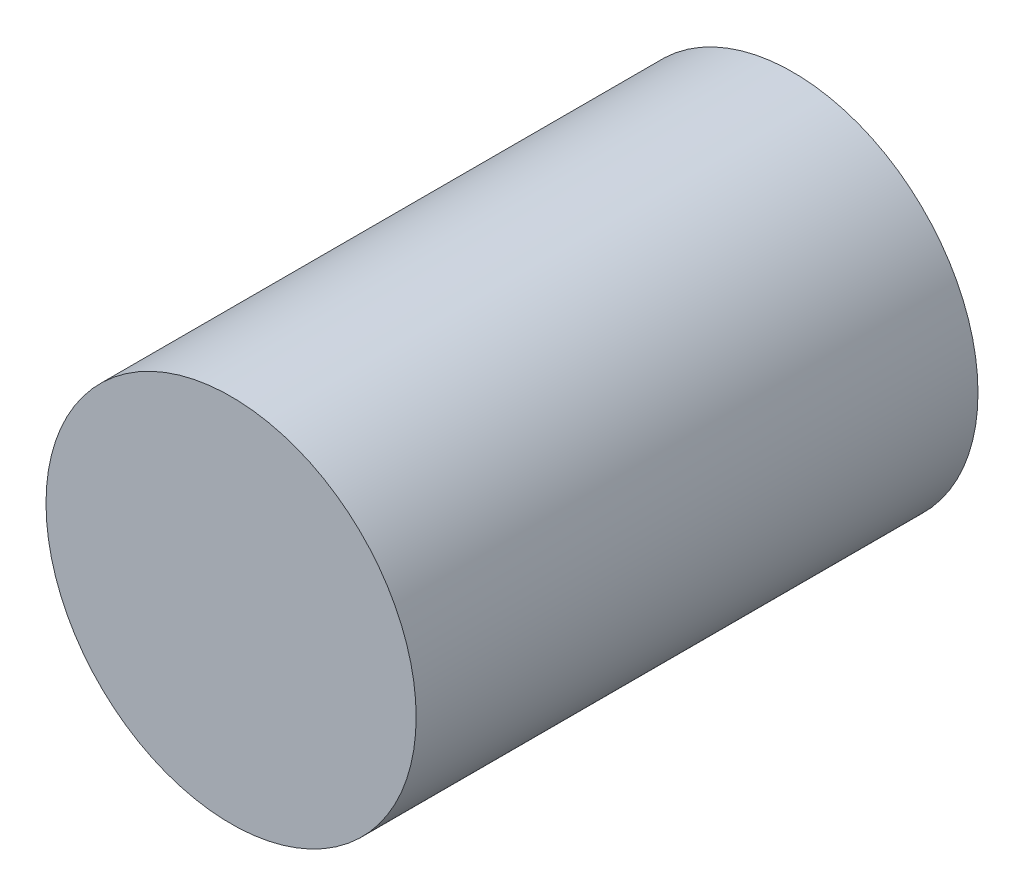
SolidWorks part; units mm, degrees
ref_plane "前视基准面" through (0, 0, 0) normal (0, 0, 1) x (1, 0, 0)
ref_plane "上视基准面" through (0, 0, 0) normal (0, 1, 0) x (1, 0, 0)
ref_plane "右视基准面" through (0, 0, 0) normal (1, 0, 0) x (0, 0, -1)
other "Configuration Table"
sketch "草图1" plane through (0, 0, 0) normal (0, 0, 1) x (1, 0, 0)
  circle A0 centre (0, 0) radius 28
extrude "solid_obs_03_outer_cylinder" add sketch "草图1" along normal blind 85
